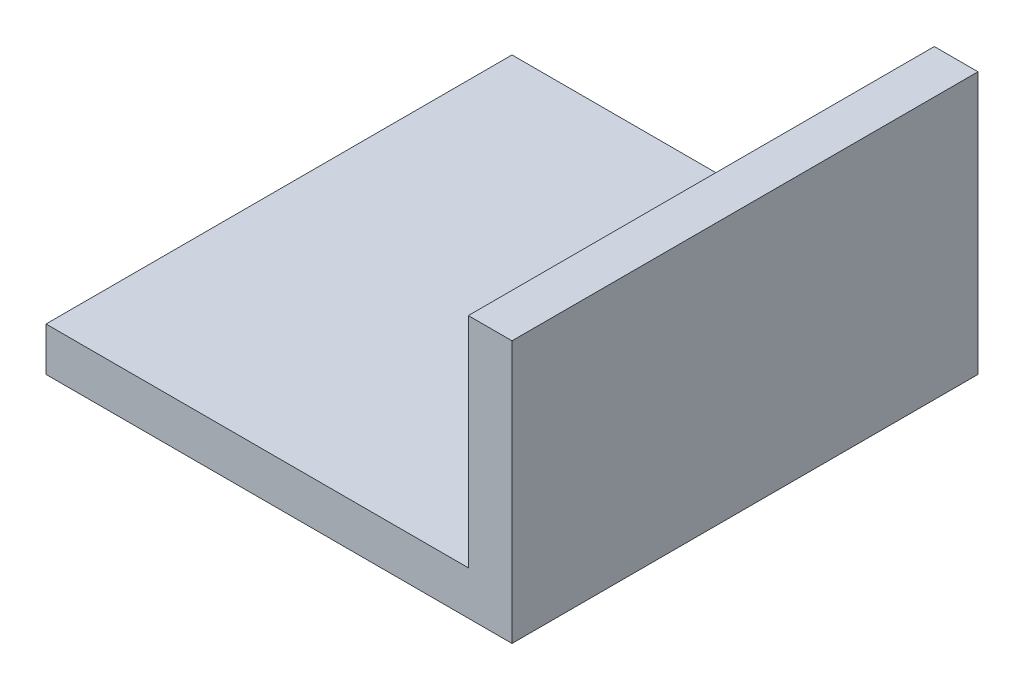
SolidWorks part; units mm, degrees
ref_plane "Front Plane" through (0, 0, 0) normal (0, 0, 1) x (1, 0, 0)
ref_plane "Top Plane" through (0, 0, 0) normal (0, 1, 0) x (1, 0, 0)
ref_plane "Right Plane" through (0, 0, 0) normal (1, 0, 0) x (0, 0, -1)
sketch "Sketch3" plane through (0, 0, 0) normal (0, 0, 1) x (1, 0, 0)
  line L0 (-20.1535, 2.3527) -> (-20.1535, 30.9277)
  line L1 (-70.9535, 7.1152) -> (-24.916, 7.1152)
  line L2 (-70.9535, 7.1152) -> (-70.9535, 2.3527)
  line L7 (-20.1535, 30.9277) -> (-24.916, 30.9277)
  line L8 (-24.916, 7.1152) -> (-24.916, 30.9277)
  line L9 (-70.9535, 2.3527) -> (-20.1535, 2.3527)
  dimension "D1" = 50.8
  dimension "D2" = 28.575
  dimension "D3" = 4.7625
  dimension "D4" = 4.7625
extrude "Boss-Extrude1" add sketch "Sketch3" along normal blind 50.8
